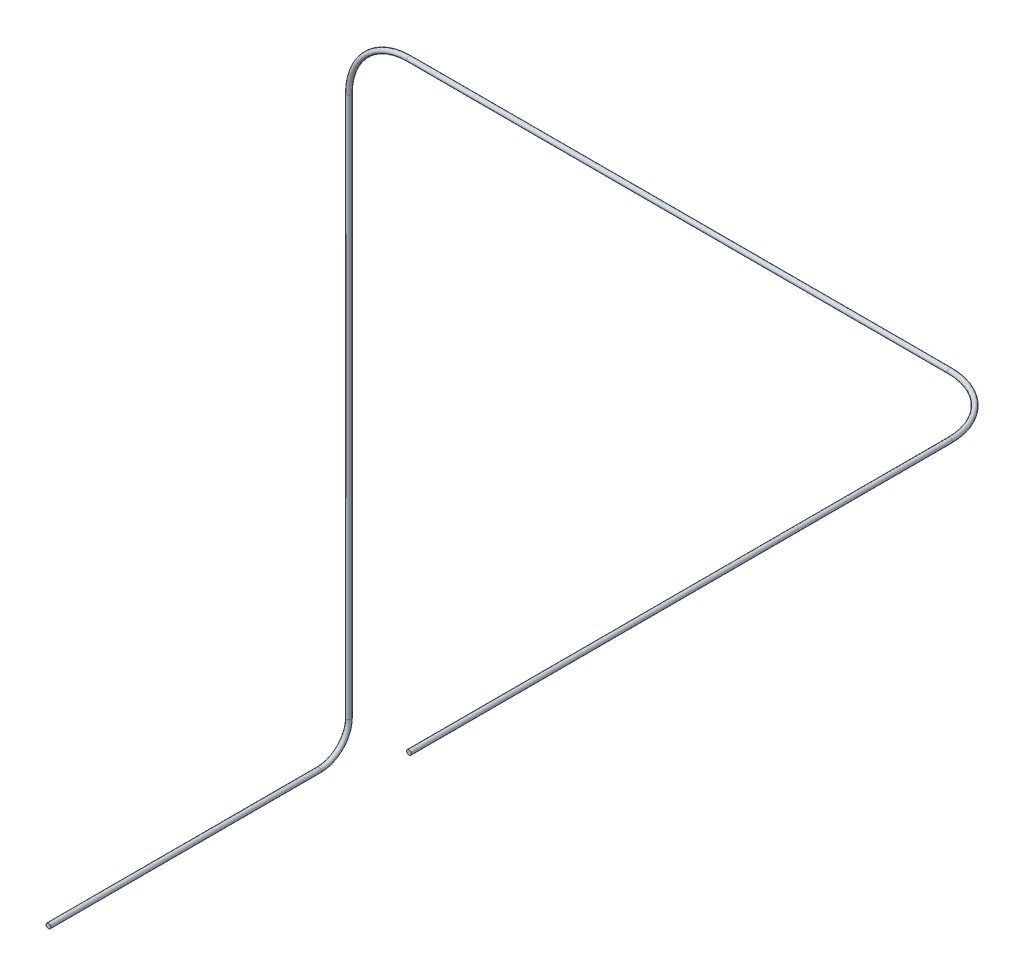
SolidWorks part; units mm, degrees
ref_plane "Front Plane" through (0, 0, 0) normal (0, 0, 1) x (1, 0, 0)
ref_plane "Top Plane" through (0, 0, 0) normal (0, 1, 0) x (1, 0, 0)
ref_plane "Right Plane" through (0, 0, 0) normal (1, 0, 0) x (0, 0, -1)
sketch3d "3DSketch1"
  line L0 (0, 0, 0) -> (0, 0, -450)
  line L1 (-50, 0, -500) -> (-500, 0, -500)
  line L2 (-550, -50, -500) -> (-550, -500, -500)
  line L3 (-550, -525, -475) -> (-550, -525, -250)
  arc A0 (-500, 0, -500) -> (-550, -50, -500) centre (-500, -50, -500) ccw
  arc A1 (0, 0, -450) -> (-50, 0, -500) centre (-50, 0, -450) ccw
  arc A2 (-550, -525, -475) -> (-550, -500, -500) centre (-550, -500, -475) ccw
  point P7 (-550, 0, -500)
  point P8 (-500, -50, -450)
  point P11 (0, 0, -500)
  point P12 (-50, 50, -450)
  point P16 (-550, -525, -500)
  point P17 (-525, -500, -475)
  dimension "D2" = 50
  dimension "D3" = 250
  dimension "D4" = 25
  dimension "D1" = 500
sketch "Sketch1" plane through (0, 0, 0) normal (0, 0, 1) x (1, 0, 0)
  circle A0 centre (0, 0) radius 2
  dimension "D1" = 4
sweep "Sweep1" add profiles "Sketch1" path "3DSketch1"
